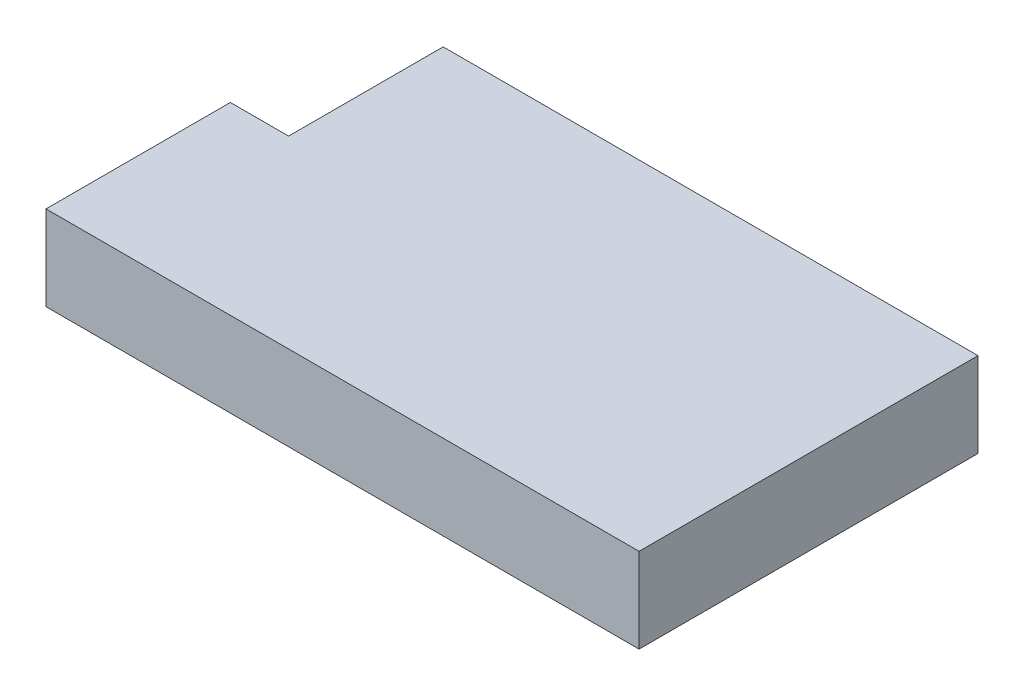
SolidWorks part; units mm, degrees
material "K110"
ref_plane "Front Plane" through (0, 0, 0) normal (0, 0, 1) x (1, 0, 0)
ref_plane "Top Plane" through (0, 0, 0) normal (0, 1, 0) x (1, 0, 0)
ref_plane "Right Plane" through (0, 0, 0) normal (1, 0, 0) x (0, 0, -1)
sketch "Sketch1" plane through (0, 0, 0) normal (0, 1, 0) x (1, 0, 0)
  line L1 (-105, -60) -> (105, -60)
  line L2 (-105, -60) -> (-105, 60)
  line L3 (-105, 60) -> (105, 60)
  line L4 (105, -60) -> (105, 60)
  line L5 (-105, -60) -> (105, 60) construction
  line L6 (-105, 60) -> (105, -60) construction
  point P0 (0, 0)
  dimension "D1" = 120
  dimension "D2" = 210
extrude "Boss-Extrude1" add sketch "Sketch1" against normal blind 30
sketch "Sketch2" plane through (0, 0, 0) normal (0, 1, 0) x (1, 0, 0)
  line L1 (-105, 60) -> (-84.3675, 60)
  line L2 (-105, 60) -> (-105, 5.27)
  line L3 (-105, 5.27) -> (-84.3675, 5.27)
  line L4 (-84.3675, 60) -> (-84.3675, 5.27)
  line L5 (-85, -14.72) -> (-84.3675, 5.27) construction
  line L10 (-65, 0.28) -> (-84.3675, 5.27) construction
  dimension "D1" = 20
extrude "Cut-Extrude1" cut sketch "Sketch2" against normal up to next
